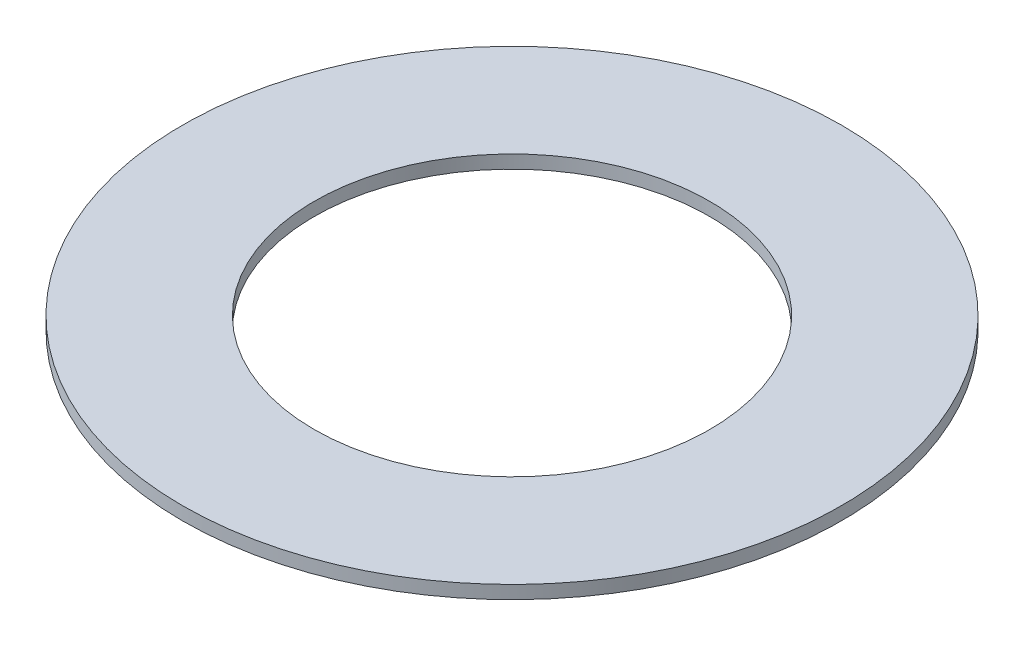
SolidWorks part; units mm, degrees
ref_plane "Front" through (0, 0, 0) normal (0, 0, 1) x (1, 0, 0)
ref_plane "Top" through (0, 0, 0) normal (0, 1, 0) x (1, 0, 0)
ref_plane "Right" through (0, 0, 0) normal (1, 0, 0) x (0, 0, -1)
sketch "Sketch1" plane through (0, 0, 0) normal (0, 1, 0) x (1, 0, 0)
  circle A0 centre (0, 0) radius 5
  circle A1 centre (0, 0) radius 3
  dimension "D1" = 10
  dimension "D2" = 6
extrude "Boss-Extrude1" add sketch "Sketch1" along normal blind 0.2 contours A1 | A0
